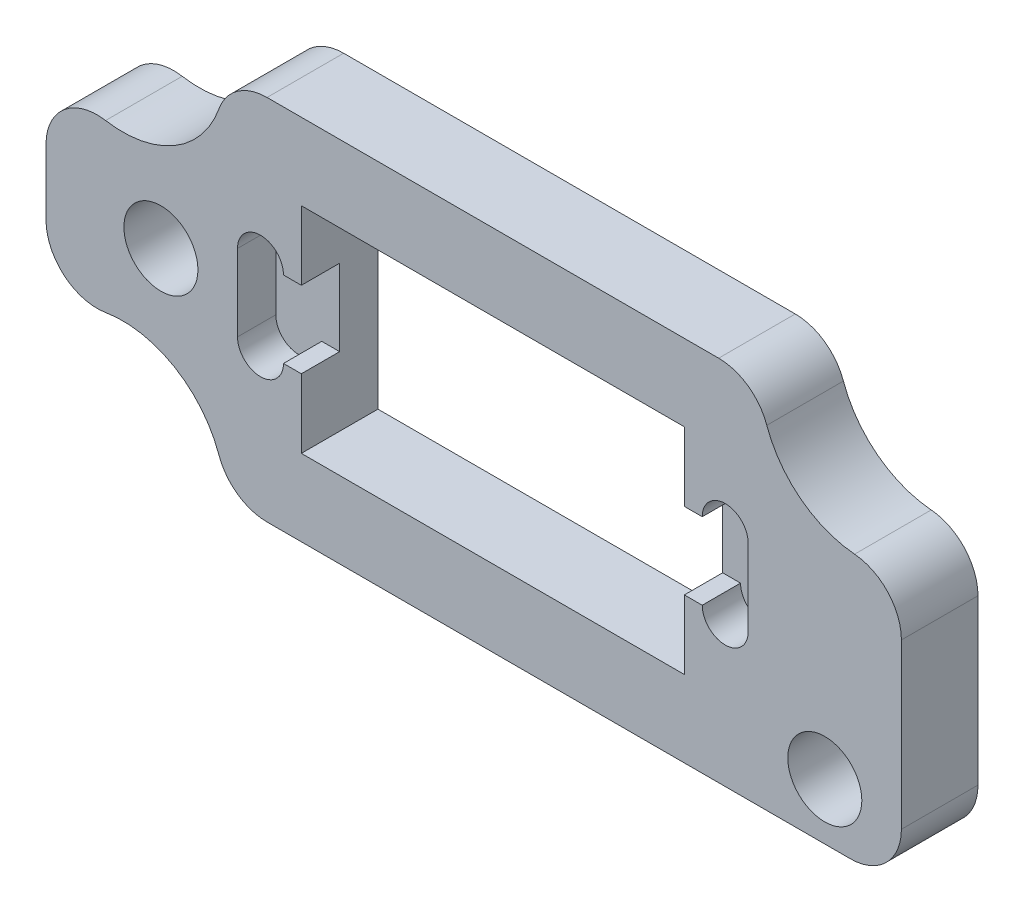
SolidWorks part; units mm, degrees
material "Thornel Mat VMA"
ref_plane "前视基准面" through (0, 0, 0) normal (0, 0, 1) x (1, 0, 0)
ref_plane "上视基准面" through (0, 0, 0) normal (0, 1, 0) x (1, 0, 0)
ref_plane "右视基准面" through (0, 0, 0) normal (1, 0, 0) x (0, 0, -1)
sketch "草图1" plane through (0, 0, 0) normal (0, 0, 1) x (1, 0, 0)
  line L1 (-7.5, -4.2) -> (7.5, -4.2)
  line L2 (-7.5, -4.2) -> (-7.5, 4.2)
  line L3 (-7.5, 4.2) -> (7.5, 4.2)
  line L4 (7.5, -4.2) -> (7.5, 4.2)
  line L5 (-7.5, -4.2) -> (7.5, 4.2) construction
  line L6 (-7.5, 4.2) -> (7.5, -4.2) construction
  line L7 (-17.5, -7.2) -> (17.5, -7.2)
  line L8 (-17.5, -7.2) -> (-17.5, 7.2)
  line L9 (-17.5, 7.2) -> (17.5, 7.2)
  line L10 (17.5, -7.2) -> (17.5, 7.2)
  line L11 (-17.5, -7.2) -> (17.5, 7.2) construction
  line L12 (-17.5, 7.2) -> (17.5, -7.2) construction
  point P0 (0, 0)
  point P6 (0, 0)
  dimension "D1" = 8.4
  dimension "D2" = 15
  dimension "D3" = 3
  dimension "D4" = 10
extrude "凸台-拉伸1" add sketch "草图1" along normal blind 3
sketch "草图2" plane through (0, 0, 3) normal (0, 0, 1) x (1, 0, 0)
  line L1 (-10, -1.5) -> (10, -1.5)
  line L2 (-10, -1.5) -> (-10, 1.5)
  line L3 (-10, 1.5) -> (10, 1.5)
  line L4 (10, -1.5) -> (10, 1.5)
  line L5 (-10, -1.5) -> (10, 1.5) construction
  line L6 (-10, 1.5) -> (10, -1.5) construction
  point P0 (0, 0)
  dimension "D1" = 20
  dimension "D2" = 3
extrude "切除-拉伸1" cut sketch "草图2" against normal blind 1.5
sketch "草图3" plane through (0, 0, 3) normal (0, 0, 1) x (1, 0, 0)
  line L0 (-17.5, 0) -> (17.5, 0) construction
  line L1 (-17.5, 7.2) -> (-17.5, -7.2) construction
  line L2 (17.5, -7.2) -> (17.5, 7.2) construction
  circle A0 centre (-13, 0) radius 1.45
  circle A1 centre (13, 0) radius 1.6 construction
  dimension "D1" = 13
  dimension "D2" = 2.9
  dimension "D3" = 13
  dimension "D4" = 3.2
extrude "切除-拉伸2" cut sketch "草图3" against normal blind 20
sketch "草图5" plane through (0, 0, 3) normal (0, 0, 1) x (1, 0, 0)
  line L0 (17.5, 7.2) -> (-17.5, 7.2) construction
  line L1 (-17.5, 7.2) -> (-17.5, -7.2) construction
  line L2 (0, 7.2) -> (0, -7.2) construction
  line L3 (-17.5, -7.2) -> (17.5, -7.2) construction
  line L4 (-17.5, 0) -> (17.5, 0) construction
  line L5 (17.5, -7.2) -> (17.5, 7.2) construction
  circle A0 centre (-14.5, 7.2) radius 4
  circle A1 centre (14.5, 7.2) radius 4
  circle A2 centre (14.5, -7.2) radius 4 construction
  circle A3 centre (-14.5, -7.2) radius 4
  dimension "D1" = 3
  dimension "D2" = 8
extrude "切除-拉伸4" cut sketch "草图5" against normal blind 10
sketch "草图9" plane through (0, 0, 3) normal (0, 0, 1) x (1, 0, 0)
  line L1 (17.5, -7.2) -> (16, -7.2)
  line L2 (17.5, -7.2) -> (17.5, 7.2)
  line L3 (17.5, 7.2) -> (16, 7.2)
  line L4 (16, -7.2) -> (16, 7.2)
  dimension "D1" = 1.5
  dimension "D2" = 14.4
extrude "切除-拉伸7" cut sketch "草图9" against normal through all
fillet "圆角2" radius 2 7 edges at (-10.5, -7.2, 1.5) (10.5, 7.2, 1.5) (-17.5, 4.5542, 1.5) (-17.5, -4.5542, 1.5) (-10.5, 7.2, 1.5) (16, -7.2, 1.5) (16, 3.4919, 1.5)
sketch "草图6" plane through (0, 0, 3) normal (0, 0, 1) x (1, 0, 0)
  line L0 (-7.5, 1.5) -> (-10, 1.5) construction
  line L1 (-10, -1.5) -> (-7.5, -1.5) construction
  line L2 (10, 1.5) -> (7.5, 1.5) construction
  line L3 (7.5, -1.5) -> (10, -1.5) construction
  circle A0 centre (-9.1, 1.5) radius 0.9
  circle A1 centre (-9.1, -1.5) radius 0.9
  circle A2 centre (9.1, 1.5) radius 0.9
  circle A3 centre (9.1, -1.5) radius 0.9
  dimension "D1" = 1.8
extrude "切除-拉伸5" cut sketch "草图6" against normal blind 1.5
sketch "草图7" plane through (0, 0, 3) normal (0, 0, 1) x (1, 0, 0)
  line L0 (0, 0) -> (13, 0) construction
  line L1 (13, 0) -> (13, -5) construction
  circle A0 centre (13, -5) radius 1.45
  dimension "D3" = 2.9
  dimension "D1" = 13
  dimension "D2" = 5
extrude "切除-拉伸6" cut sketch "草图7" against normal through all
